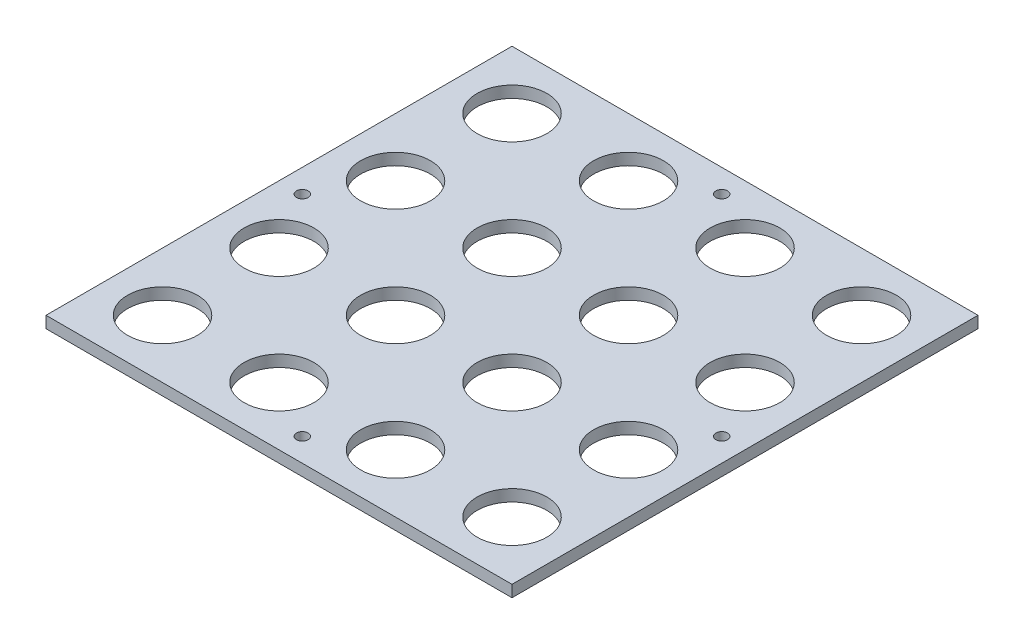
SolidWorks part; units mm, degrees
ref_plane "Front" through (0, 0, 0) normal (0, 0, 1) x (1, 0, 0)
ref_plane "Top" through (0, 0, 0) normal (0, 1, 0) x (1, 0, 0)
ref_plane "Right" through (0, 0, 0) normal (1, 0, 0) x (0, 0, -1)
sketch "Sketch1" plane through (0, 0, 0) normal (0, 1, 0) x (1, 0, 0)
  line L1 (-127, 127) -> (127, 127)
  line L2 (-127, 127) -> (-127, -127)
  line L3 (-127, -127) -> (127, -127)
  line L4 (127, 127) -> (127, -127)
  line L5 (-127, 127) -> (127, -127) construction
  line L6 (-127, -127) -> (127, 127) construction
  circle A0 centre (-95.25, 95.25) radius 19
  circle A1 centre (-31.75, 95.25) radius 19
  circle A2 centre (31.75, 95.25) radius 19
  circle A3 centre (95.25, 95.25) radius 19
  circle A8 centre (-31.75, 31.75) radius 19
  circle A9 centre (31.75, 31.75) radius 19
  circle A10 centre (95.25, 31.75) radius 19
  circle A15 centre (-31.75, -31.75) radius 19
  circle A16 centre (31.75, -31.75) radius 19
  circle A17 centre (95.25, -31.75) radius 19
  circle A22 centre (-31.75, -95.25) radius 19
  circle A23 centre (31.75, -95.25) radius 19
  circle A24 centre (95.25, -95.25) radius 19
  circle A57 centre (-95.25, 31.75) radius 19
  circle A58 centre (-95.25, -31.75) radius 19
  circle A59 centre (-95.25, -95.25) radius 19
  circle A62 centre (-114.3, 0) radius 3.175
  circle A63 centre (114.3, 0) radius 3.175
  circle A64 centre (0, 114.3) radius 3.175
  circle A65 centre (0, -114.3) radius 3.175
  point P0 (0, 0)
  dimension "D3" = 38
  dimension "D4" = 31.75
  dimension "D8" = 6.35
  dimension "D9" = 12.7
  dimension "D10" = 6.35
  dimension "D11" = 12.7
  dimension "D12" = 6.35
  dimension "D14" = 6.35
  dimension "D1" = 254
  dimension "D2" = 254
  dimension "D5" = 31.75
  dimension "D13" = 12.7
  dimension "D15" = 12.7
  dimension "D6" = 4
  dimension "D7" = 4
extrude "Boss-Extrude2" add sketch "Sketch1" along normal blind 6.35
